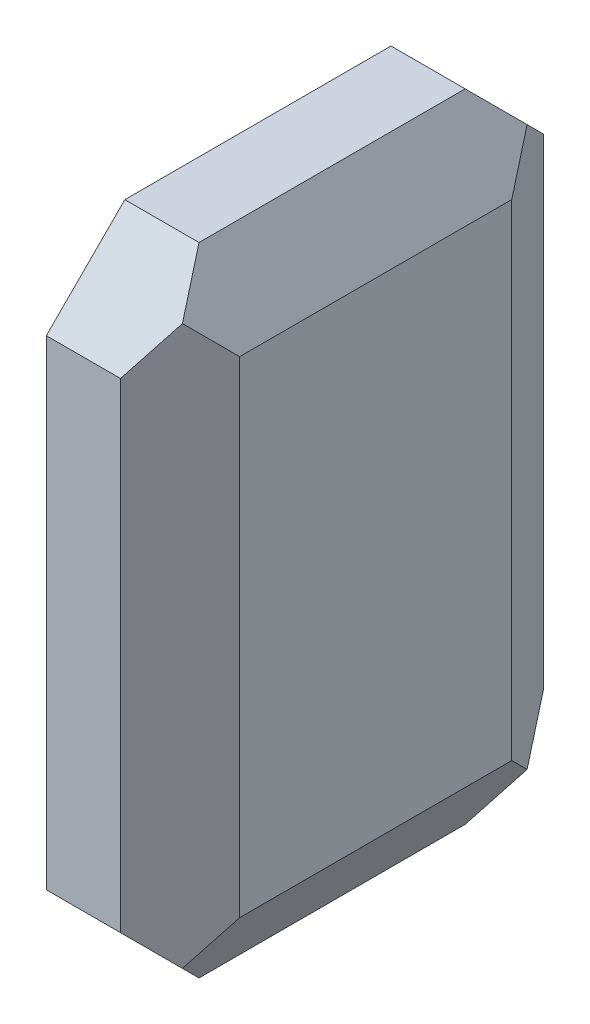
SolidWorks part; units mm, degrees
material "6061 Alloy"
ref_plane "Front Plane" through (0, 0, 0) normal (1, 0, 0) x (0, 1, 0)
ref_plane "Top Plane" through (0, 0, 0) normal (0, 0, 1) x (0, 1, 0)
ref_plane "Right Plane" through (0, 0, 0) normal (0, 1, 0) x (-1, 0, 0)
sketch "Sketch1" plane through (0, 0, 0) normal (1, 0, 0) x (0, 1, 0)
  line L0 (0, 0) -> (37.084, 0)
  line L1 (37.084, 0) -> (37.084, -24.638)
  line L2 (37.084, -24.638) -> (0, -24.638)
  line L3 (0, -24.638) -> (0, 0)
  point P3 (57.4584, -24.638)
  dimension "D1" = 24.638
  dimension "D2" = 37.084
extrude "Boss-Extrude1" add sketch "Sketch1" along normal blind 6.858
chamfer "Chamfer2" distance 4.572 angle 45 4 edges at (3.429, 0, 0) (3.429, 0, -24.638) (3.429, 37.084, 0) (3.429, 37.084, -24.638)
chamfer "Chamfer3" distance 2.54 angle 60 2 edges at (6.858, 18.542, 0) (6.858, 18.542, -24.638)
chamfer "Chamfer4" distance 2.54 angle 60 2 edges at (6.858, 0, -12.319) (6.858, 37.084, -12.319)
sketch "Sketch3" plane through (0, 0, 0) normal (-1, 0, 0) x (0, -1, 0)
  line L0 (-32.512, 0) -> (-4.572, 0) construction
  line L1 (-28.542, -22.319) -> (-8.542, -22.319) construction
  line L2 (-28.542, -22.319) -> (-28.542, -2.319) construction
  line L3 (-28.542, -2.319) -> (-8.542, -2.319) construction
  line L4 (-8.542, -22.319) -> (-8.542, -2.319) construction
  line L5 (-28.542, -22.319) -> (-8.542, -2.319) construction
  line L6 (-28.542, -2.319) -> (-8.542, -22.319) construction
  line L7 (-37.084, -20.066) -> (-37.084, -4.572) construction
  circle A0 centre (-8.542, -2.319) radius 1
  circle A1 centre (-8.542, -22.319) radius 1
  circle A2 centre (-28.542, -22.319) radius 1
  circle A3 centre (-28.542, -2.319) radius 1
  point P0 (-18.542, -12.319)
  point P8 (-18.542, 0)
  point P11 (-37.084, -12.319)
  point P21 (-18.542, -12.319)
  dimension "D2" = 2
  dimension "D1" = 20
  dimension "D3" = 4
extrude "Cut-Extrude1" cut sketch "Sketch3" against normal blind 2.54 and the other way through all
